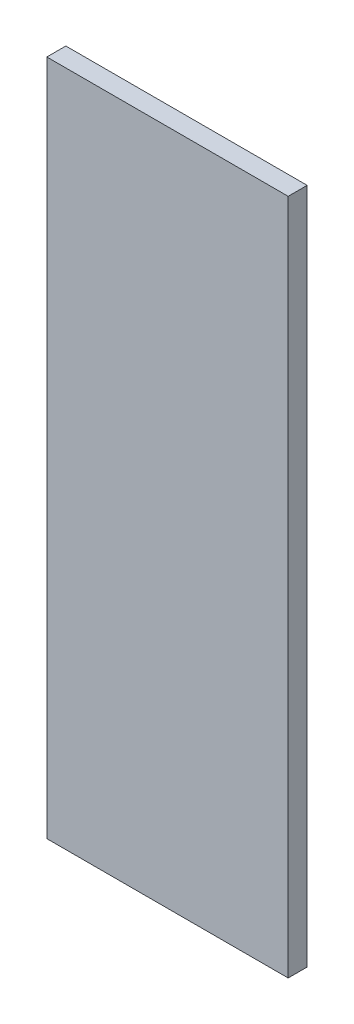
SolidWorks part; units mm, degrees
ref_plane "Front Plane" through (0, 0, 0) normal (0, 0, 1) x (1, 0, 0)
ref_plane "Top Plane" through (0, 0, 0) normal (0, 1, 0) x (1, 0, 0)
ref_plane "Right Plane" through (0, 0, 0) normal (1, 0, 0) x (0, 0, -1)
sketch "Sketch1" plane through (0, 0, 0) normal (0, 0, 1) x (1, 0, 0)
  line L1 (0, 0) -> (20.32, 0)
  line L2 (0, 0) -> (0, 57)
  line L3 (0, 57) -> (20.32, 57)
  line L4 (20.32, 0) -> (20.32, 57)
  dimension "D1" = 20.32
  dimension "D2" = 57
extrude "Boss-Extrude1" add sketch "Sketch1" along normal blind 1.6
sketch "Sketch2" plane through (0, 0, 1.6) normal (0, 0, 1) x (1, 0, 0)
  line L1 (0, 0) -> (20.32, 0) construction
  line L2 (6.6831, 0) -> (15.1, 0)
  line L3 (6.6831, 0) -> (6.6831, 4)
  line L4 (6.6831, 4) -> (15.1, 4)
  line L5 (15.1, 0) -> (15.1, 4)
  dimension "D1" = 4
extrude "Boss-Extrude2" add sketch "Sketch2" against normal blind 6
